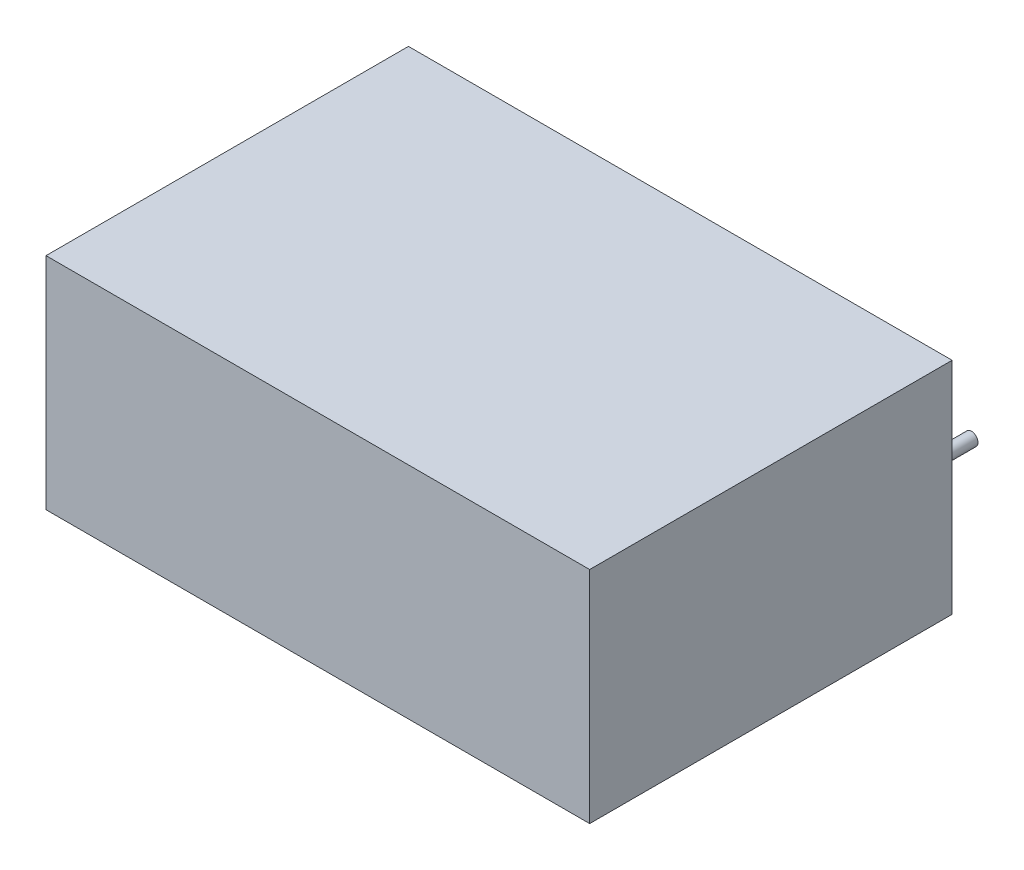
SolidWorks part; units mm, degrees
ref_plane "Front" through (0, 0, 0) normal (0, 0, 1) x (1, 0, 0)
ref_plane "Top" through (0, 0, 0) normal (0, 1, 0) x (1, 0, 0)
ref_plane "Right" through (0, 0, 0) normal (1, 0, 0) x (0, 0, -1)
sketch "Эскиз1" plane through (0, 0, 0) normal (0, 0, 1) x (1, 0, 0)
  line L1 (-0.8, -0.8) -> (0.8, -0.8)
  line L2 (-0.8, -0.8) -> (-0.8, 0.8)
  line L3 (-0.8, 0.8) -> (0.8, 0.8)
  line L4 (0.8, -0.8) -> (0.8, 0.8)
  line L5 (11.65, -0.8) -> (13.25, -0.8)
  line L6 (11.65, -0.8) -> (11.65, 0.8)
  line L7 (11.65, 0.8) -> (13.25, 0.8)
  line L8 (13.25, -0.8) -> (13.25, 0.8)
sketch "Эскиз2" plane through (0, 0, 0) normal (0, 0, 1) x (1, 0, 0)
  line L0 (-0.5, 8) -> (-0.5, -9)
  line L1 (41.5, -9) -> (41.5, 8)
  line L2 (-0.5, -9) -> (41.5, -9)
  line L3 (41.5, 8) -> (-0.5, 8)
  dimension "D1" = 42
  dimension "D2" = 17
  dimension "D3" = 8
  dimension "D4" = 0.5
extrude "Вытянуть1" add sketch "Эскиз2" along normal blind 28
sketch "Эскиз3" plane through (0, 0, 0) normal (0, 0, -1) x (-1, 0, 0)
  line L0 (-20.5, 10.0175) -> (-20.5, -10.945) construction
  line L1 (-32.2826, -0.5) -> (4.828, -0.5) construction
  line L2 (-41.5, 8) -> (0.5, 8) construction
  line L3 (0.5, -9) -> (-41.5, -9) construction
  line L4 (-41.5, -9) -> (-41.5, 8) construction
  line L5 (0.5, 8) -> (0.5, -9) construction
  circle A0 centre (-2, -0.5) radius 0.5
  circle A1 centre (-39, -0.5) radius 0.5
  dimension "D1" = 37
extrude "Вытянуть2" add sketch "Эскиз3" along normal blind 4
